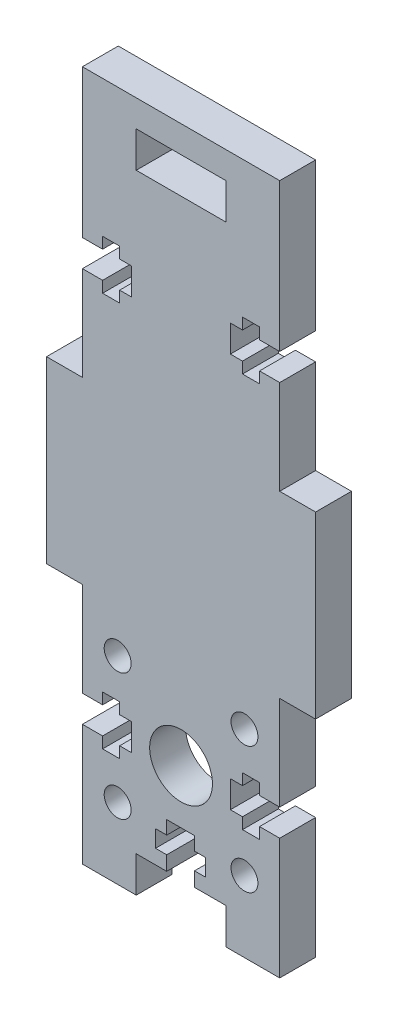
SolidWorks part; units mm, degrees
ref_plane "Front Plane" through (0, 0, 0) normal (0, 0, 1) x (1, 0, 0)
ref_plane "Top Plane" through (0, 0, 0) normal (0, 1, 0) x (1, 0, 0)
ref_plane "Right Plane" through (0, 0, 0) normal (1, 0, 0) x (0, 0, -1)
sketch "Sketch1" plane through (0, 0, 0) normal (0, 0, 1) x (1, 0, 0)
  line L0 (20, 6) -> (0, 6) construction
  line L1 (0, 0) -> (20, 0) construction
  line L2 (0, 0) -> (0, 12) construction
  line L3 (0, 12) -> (20, 12) construction
  line L4 (20, 0) -> (20, 12) construction
  line L5 (-1, 21) -> (21, 21)
  line L6 (-1, 21) -> (-1, -53)
  line L7 (-1, -53) -> (21, -53)
  line L8 (21, 21) -> (21, -53)
  line L13 (10, 6) -> (10, -53) construction
  line L14 (1.6753, -38) -> (20, -38) construction
  line L15 (10, -38) -> (-1.5613, -26.4387) construction
  line L16 (10, 21) -> (10, -53) construction
  line L17 (21, -16) -> (-55.7216, -16) construction
  circle A1 centre (10, -38) radius 3.5
  dimension "D3" = 7
  dimension "D1" = 20
  dimension "D2" = 12
  dimension "D4" = 44
  dimension "D5" = 15
  dimension "D6" = 15
  dimension "D7" = 11
  dimension "D8" = 11
extrude "Sheet Thickness" add sketch "Sketch1" along normal blind 4
sketch "Sketch2" plane through (0, 0, 4) normal (0, 0, 1) x (1, 0, 0)
  line L0 (10, -38) -> (-9.2287, -38) construction
  line L1 (10, -38) -> (2.9289, -30.9289) construction
  line L2 (21, -53) -> (21, 21) construction
  circle A0 centre (10, -38) radius 3.5 construction
  circle A1 centre (10, -38) radius 3.5
  circle A2 centre (2.9289, -30.9289) radius 1.5
  circle A3 centre (17.0711, -30.9289) radius 1.5
  circle A4 centre (17.0711, -45.0711) radius 1.5
  circle A5 centre (2.9289, -45.0711) radius 1.5
  point P3 (6.5, -38)
  point P16 (10, -38)
  dimension "D2" = 3
  dimension "D1" = 45
  dimension "D3" = 10
  dimension "D5" = 11
  dimension "D4" = 4
extrude "Bearing Holder Mounting" cut sketch "Sketch2" against normal blind 4
sketch "Sketch3" plane through (0, 0, 4) normal (0, 0, 1) x (1, 0, 0)
  line L0 (-1, -16) -> (41.4514, -16) construction
  line L1 (-1, 21) -> (-1, -53) construction
  line L2 (10, 21) -> (10, -64.2044) construction
  line L3 (21, 21) -> (-1, 21) construction
  line L4 (-1, -38) -> (4.5, -38) construction
  line L5 (-1, -36.5) -> (4.5, -36.5)
  line L6 (-1, -36.5) -> (-1, -39.5)
  line L7 (-1, -39.5) -> (4.5, -39.5)
  line L8 (4.5, -36.5) -> (4.5, -39.5)
  line L9 (1.25, -35.25) -> (3.15, -35.25)
  line L10 (1.25, -35.25) -> (1.25, -40.75)
  line L11 (1.25, -40.75) -> (3.15, -40.75)
  line L12 (3.15, -35.25) -> (3.15, -40.75)
  line L13 (10, -38) -> (8.4395, -38) construction
  line L14 (21, -39.5) -> (15.5, -39.5)
  line L15 (15.5, -36.5) -> (15.5, -39.5)
  line L16 (21, -36.5) -> (15.5, -36.5)
  line L17 (21, -36.5) -> (21, -39.5)
  line L18 (18.75, -40.75) -> (16.85, -40.75)
  line L19 (16.85, -35.25) -> (16.85, -40.75)
  line L20 (18.75, -35.25) -> (16.85, -35.25)
  line L21 (18.75, -35.25) -> (18.75, -40.75)
  line L22 (10, 6) -> (8.4395, 6) construction
  line L23 (-1, 6) -> (4.5, 6) construction
  line L24 (18.75, 3.25) -> (18.75, 8.75)
  line L25 (18.75, 3.25) -> (16.85, 3.25)
  line L26 (16.85, 3.25) -> (16.85, 8.75)
  line L27 (18.75, 8.75) -> (16.85, 8.75)
  line L28 (21, 4.5) -> (21, 7.5)
  line L29 (21, 4.5) -> (15.5, 4.5)
  line L30 (15.5, 4.5) -> (15.5, 7.5)
  line L31 (21, 7.5) -> (15.5, 7.5)
  line L32 (3.15, 3.25) -> (3.15, 8.75)
  line L33 (1.25, 8.75) -> (3.15, 8.75)
  line L34 (1.25, 3.25) -> (1.25, 8.75)
  line L35 (1.25, 3.25) -> (3.15, 3.25)
  line L36 (4.5, 4.5) -> (4.5, 7.5)
  line L37 (-1, 7.5) -> (4.5, 7.5)
  line L38 (-1, 4.5) -> (-1, 7.5)
  line L39 (-1, 4.5) -> (4.5, 4.5)
  line M17 (-1, 21) -> (-1, -53)
  line M19 (21, -53) -> (21, 21)
  dimension "D1" = 1.9
  dimension "D2" = 5.5
  dimension "D3" = 3
  dimension "D4" = 2.75
  dimension "D5" = 5.5
  dimension "D6" = 2.25
extrude "Nut Mounting" cut sketch "Sketch3" against normal blind 4 contours L39 L34 L35 L32 | L34 L37 L32 L33 | L26 L31 L30 L29 | L24 L31 L26 L29 | L31 L24 L29 M19 | L31 L24 L27 L26 | L24 L29 L26 L25 | L16 L21 L14 M19 | L21 L16 L19 L14 | L19 L16 L15 L14 | L21 L20 L19 L16 | L21 L14 L19 L18 | L12 L5 L10 L7 | L5 L12 L7 L8 | L12 L9 L10 L5 | L10 L5 L7 M17 | L12 L7 L10 L11
sketch "Sketch5" plane through (0, 0, 4) normal (0, 0, 1) x (1, 0, 0)
  line L0 (10, 21) -> (10, 7.4999) construction
  line L1 (21, 21) -> (-1, 21) construction
  line L2 (5, 21) -> (15, 21)
  line L3 (5, 21) -> (5, 17)
  line L4 (15, 21) -> (15, 17)
  line L5 (5, 17) -> (15, 17)
  line L6 (-1, 21) -> (-1, 7.5) construction
  line L7 (-1, -16) -> (21, -16) construction
  line L8 (-1, 4.5) -> (-1, -36.5) construction
  line L9 (21, -36.5) -> (21, 4.5) construction
  line L10 (15, -53) -> (15, -49)
  line L11 (5, -49) -> (15, -49)
  line L12 (5, -53) -> (5, -49)
  line L13 (5, -53) -> (15, -53)
  dimension "D1" = 10
  dimension "D2" = 6
  dimension "D3" = 4
extrude "Top Slots" cut sketch "Sketch5" against normal blind 4 contours L12 L13 L10 L11 | L2 L3 L5 L4
sketch "Sketch9" plane through (-1, 0, 0) normal (-1, 0, 0) x (0, 0, 1)
  line L0 (0, 4.5) -> (0, -36.5) construction
  line L1 (0, -6) -> (4, -6)
  line L2 (0, -6) -> (0, -26)
  line L3 (0, -26) -> (4, -26)
  line L4 (4, -6) -> (4, -26)
  line L5 (4, 4.5) -> (4, -36.5) construction
  point P8 (2, -26)
  point P9 (4, -16)
  dimension "D1" = 20
  dimension "D2" = 10
extrude "Boss-Extrude3" add sketch "Sketch9" along normal blind 4
sketch "Sketch10" plane through (21, 0, 0) normal (1, 0, 0) x (0, 0, -1)
  line L0 (-4, -36.5) -> (-4, 4.5) construction
  line L1 (0, -36.5) -> (0, 4.5) construction
  line L2 (-4, -6) -> (0, -6)
  line L3 (-4, -6) -> (-4, -26)
  line L4 (-4, -26) -> (0, -26)
  line L5 (0, -6) -> (0, -26)
  point P0 (-4, -16)
  dimension "D1" = 20
  dimension "D2" = 10
extrude "Boss-Extrude4" add sketch "Sketch10" along normal blind 4
sketch "Sketch11" plane through (0, 21, 0) normal (0, 1, 0) x (1, 0, 0)
  line L1 (-1, 0) -> (21, 0)
  line L2 (-1, 0) -> (-1, -4)
  line L3 (-1, -4) -> (21, -4)
  line L4 (21, 0) -> (21, -4)
extrude "Boss-Extrude5" add sketch "Sketch11" along normal blind 3
sketch "Sketch14" plane through (0, 0, 4) normal (0, 0, 1) x (1, 0, 0)
  line L0 (8.4, -49) -> (8.4, -44)
  line L6 (5, -49) -> (15, -49) construction
  line L7 (11.5, -44) -> (11.5, -49)
  line L8 (8.4, -44) -> (11.5, -44)
  line L9 (9.95, -44) -> (9.95, -50.7957) construction
  line L10 (7.15, -47.4) -> (12.75, -47.4)
  line L11 (7.15, -47.4) -> (7.15, -45.5)
  line L12 (7.15, -45.5) -> (12.75, -45.5)
  line L13 (12.75, -47.4) -> (12.75, -45.5)
  line L15 (8.4, -49) -> (11.5, -49)
  point P6 (10, -49)
  dimension "D1" = 3.1
  dimension "D2" = 1.6
  dimension "D3" = 5
  dimension "D4" = 1.9
  dimension "D5" = 1.5
  dimension "D6" = 1.25
  dimension "D7" = 1.25
extrude "Cut-Extrude4" cut sketch "Sketch14" against normal blind 10 contours L9 L8 L0 L12 | L8 L9 L12 L7 | L9 L12 L0 L10 | L12 L9 L10 L7 | L10 L9 L15 L7 | L9 L10 L0 L15 | L12 L11 L10 L0 | L10 L13 L12 L7
